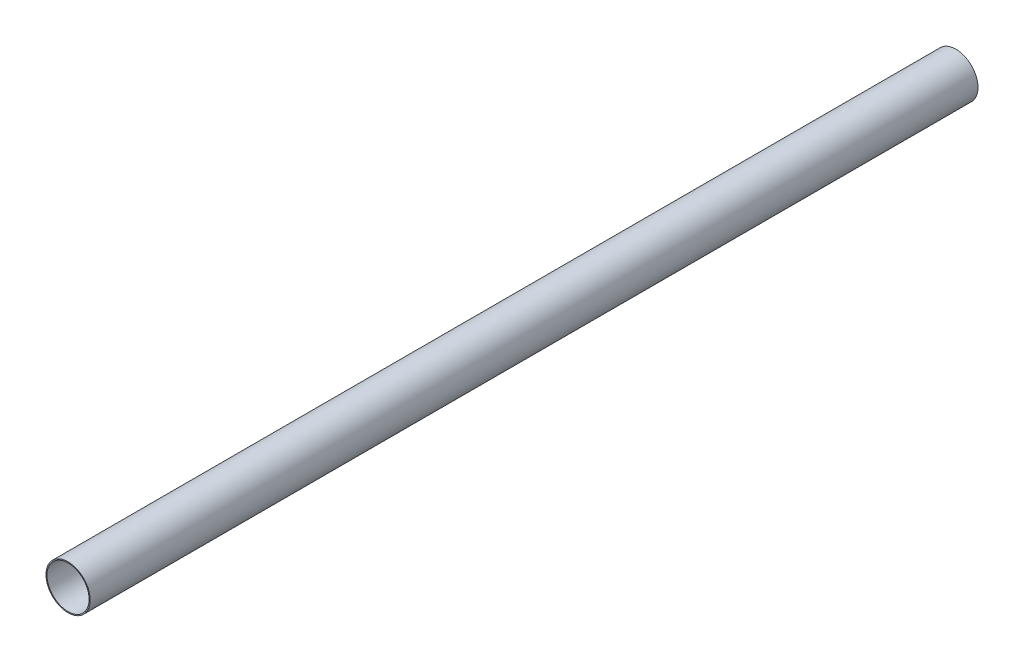
SolidWorks part; units mm, degrees
ref_plane "Front" through (0, 0, 0) normal (0, 0, 1) x (1, 0, 0)
ref_plane "Top" through (0, 0, 0) normal (0, 1, 0) x (1, 0, 0)
ref_plane "Side" through (0, 0, 0) normal (1, 0, 0) x (0, 0, -1)
other "Configuration Table"
sketch "PipeSketch" plane through (0, 0, 0) normal (0, 0, 1) x (1, 0, 0)
  circle A0 centre (0, 0) radius 136.525
  circle A1 centre (0, 0) radius 130.175
  dimension "OuterDiameter" = 273.05
  dimension "InnerDiameter" = 260.35
extrude "Extrusion" add sketch "PipeSketch" along normal blind 5486.4
sketch "FilterSketch" plane through (0, 0, 0) normal (0, 0, 1) x (1, 0, 0)
  circle A0 centre (0, 0) radius 127 construction
  dimension "NominalDiameter" = 254
